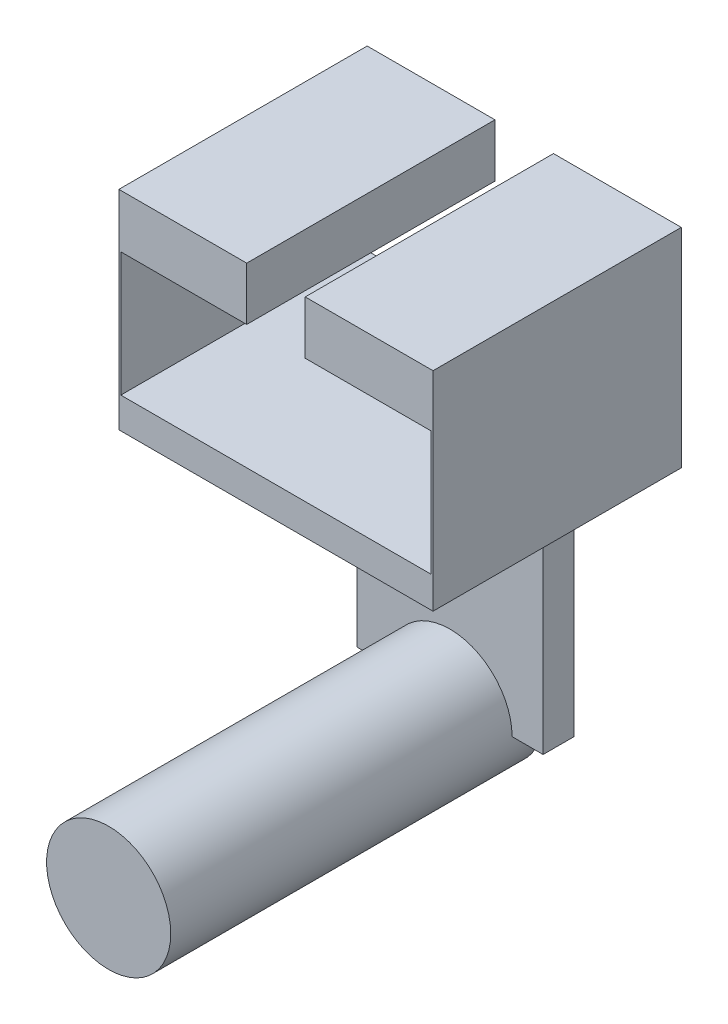
SolidWorks part; units mm, degrees
ref_plane "Front Plane" through (0, 0, 0) normal (0, 0, 1) x (1, 0, 0)
ref_plane "Top Plane" through (0, 0, 0) normal (0, 1, 0) x (1, 0, 0)
ref_plane "Right Plane" through (0, 0, 0) normal (1, 0, 0) x (0, 0, -1)
sketch "Sketch3" plane through (0, 0, 0) normal (0, 0, 1) x (1, 0, 0)
  circle A0 centre (0, 0) radius 12.7
  dimension "D1" = 25.4
extrude "Boss-Extrude1" add sketch "Sketch3" along normal blind 76.2
sketch "Sketch4" plane through (0, 0, 0) normal (0, 0, -1) x (-1, 0, 0)
  line L0 (0, 0) -> (19.05, 0)
  line L5 (19.05, 0) -> (19.05, 50.8)
  line L6 (19.05, 50.8) -> (-19.05, 50.8)
  line L7 (-19.05, 50.8) -> (-19.05, 0)
  line L8 (-19.05, 0) -> (0, 0)
  dimension "D1" = 50.8
  dimension "D2" = 38.1
extrude "Boss-Extrude2" add sketch "Sketch4" against normal blind 6.35 contours L7 L8 L0 L5 L6
sketch "Sketch6" plane through (0, 50.8, 0) normal (0, 1, 0) x (1, 0, 0)
  line L1 (-30.7019, 7.7865) -> (32.7981, 7.7865)
  line L2 (-30.7019, 7.7865) -> (-30.7019, -43.0135)
  line L3 (-30.7019, -43.0135) -> (32.7981, -43.0135)
  line L4 (32.7981, 7.7865) -> (32.7981, -43.0135)
  dimension "D1" = 63.5
  dimension "D2" = 50.8
extrude "Boss-Extrude3" add sketch "Sketch6" along normal blind 6.35
sketch "Sketch8" plane through (32.7981, 0, 0) normal (1, 0, 0) x (0, 0, -1)
  line L1 (-43.0135, 57.15) -> (7.7865, 57.15)
  line L2 (-43.0135, 57.15) -> (-43.0135, 50.8)
  line L3 (-43.0135, 50.8) -> (7.7865, 50.8)
  line L4 (7.7865, 57.15) -> (7.7865, 50.8)
sketch "Sketch9" plane through (32.7981, 0, 0) normal (1, 0, 0) x (0, 0, -1)
  line L1 (-43.0135, 57.15) -> (7.7865, 57.15)
  line L2 (-43.0135, 57.15) -> (-43.0135, 50.8)
  line L3 (-43.0135, 50.8) -> (7.7865, 50.8)
  line L4 (7.7865, 57.15) -> (7.7865, 50.8)
extrude "Boss-Extrude4" add sketch "Sketch9" along normal blind 0.3886
sketch "Sketch10" plane through (0, 57.15, 0) normal (0, 1, 0) x (1, 0, 0)
  line L0 (32.7981, -43.0135) -> (32.7981, 7.7865) construction
  line L1 (32.7981, 7.7865) -> (33.1867, 7.7865)
  line L2 (32.7981, 7.7865) -> (32.7981, -43.0135)
  line L3 (32.7981, -43.0135) -> (33.1867, -43.0135)
  line L4 (33.1867, 7.7865) -> (33.1867, -43.0135)
  line L5 (33.1867, 7.7865) -> (-30.7019, 7.7865) construction
extrude "Boss-Extrude5" add sketch "Sketch10" along normal blind 25.4
sketch "Sketch11" plane through (-30.7019, 0, 0) normal (-1, 0, 0) x (0, 0, 1)
  line L1 (-7.7865, 57.15) -> (43.0135, 57.15)
  line L2 (-7.7865, 57.15) -> (-7.7865, 50.8)
  line L3 (-7.7865, 50.8) -> (43.0135, 50.8)
  line L4 (43.0135, 57.15) -> (43.0135, 50.8)
extrude "Boss-Extrude6" add sketch "Sketch11" along normal blind 0.3886
sketch "Sketch13" plane through (0, 57.15, 0) normal (0, 1, 0) x (1, 0, 0)
  line L0 (-31.0906, -43.0135) -> (32.7981, -43.0135) construction
  line L1 (-31.0906, 7.7865) -> (-30.7019, 7.7865)
  line L2 (-31.0906, 7.7865) -> (-31.0906, -43.0135)
  line L3 (-31.0906, -43.0135) -> (-30.7019, -43.0135)
  line L4 (-30.7019, 7.7865) -> (-30.7019, -43.0135)
  dimension "D1" = 0.3886
extrude "Boss-Extrude7" add sketch "Sketch13" along normal blind 25.4
sketch "Sketch14" plane through (0, 82.55, 0) normal (0, 1, 0) x (1, 0, 0)
  line L1 (-31.0906, 7.7865) -> (-30.7019, 7.7865)
  line L2 (-31.0906, 7.7865) -> (-31.0906, -43.0135)
  line L3 (-31.0906, -43.0135) -> (-30.7019, -43.0135)
  line L4 (-30.7019, 7.7865) -> (-30.7019, -43.0135)
extrude "Boss-Extrude8" add sketch "Sketch14" along normal blind 10.8712
sketch "Sketch15" plane through (-30.7019, 0, 0) normal (1, 0, 0) x (0, 0, -1)
  line L0 (7.7865, 93.4212) -> (7.7865, 57.15) construction
  line L1 (-43.0135, 93.4212) -> (7.7865, 93.4212)
  line L2 (-43.0135, 93.4212) -> (-43.0135, 82.55)
  line L3 (-43.0135, 82.55) -> (7.7865, 82.55)
  line L4 (7.7865, 93.4212) -> (7.7865, 82.55)
  dimension "D1" = 10.8712
extrude "Boss-Extrude9" add sketch "Sketch15" along normal blind 25.7632
sketch "Sketch16" plane through (0, 82.55, 0) normal (0, 1, 0) x (1, 0, 0)
  line L1 (32.7981, 7.7865) -> (33.1867, 7.7865)
  line L2 (32.7981, 7.7865) -> (32.7981, -43.0135)
  line L3 (32.7981, -43.0135) -> (33.1867, -43.0135)
  line L4 (33.1867, 7.7865) -> (33.1867, -43.0135)
extrude "Boss-Extrude10" add sketch "Sketch16" along normal blind 10.8712
sketch "Sketch17" plane through (32.7981, 0, 0) normal (-1, 0, 0) x (0, 0, 1)
  line L0 (43.0135, 93.4212) -> (43.0135, 57.15) construction
  line L1 (-7.7865, 93.4212) -> (43.0135, 93.4212)
  line L2 (-7.7865, 93.4212) -> (-7.7865, 82.55)
  line L3 (-7.7865, 82.55) -> (43.0135, 82.55)
  line L4 (43.0135, 93.4212) -> (43.0135, 82.55)
  dimension "D1" = 10.8712
extrude "Boss-Extrude11" add sketch "Sketch17" along normal blind 25.7632
equation "\"Length_A\"= 3in"
equation "\"Diameter_A\"= 1in"
equation "\"Width_B\"= 1.5in"
equation "\"Length_B\"= 2in"
equation "\"Thickness_B\"= 0.25in"
equation "\"Length_C\"= 2.5in"
equation "\"Base_C\"= 2in"
equation "\"Height_C\"= 0.250in"
equation "\"Length_D\"= 2in"
equation "\"Base_D\"= 1.498in"
equation "\"Thickness_D\"=0.0153"
equation "\"Length_E\"= 2in"
equation "\"Base_E\"= 0.9990"
equation "\"Height_E\"= 0.428in"
equation "\"Sy\"= 36000"
equation "\"E\"= 29000000"
equation "\"deflection\"= 0.005in"
equation "\"D1@Sketch3\"=\"Diameter_A\""
equation "\"D1@Boss-Extrude1\"=\"Length_A\""
equation "\"D1@Sketch4\"=\"Length_B\""
equation "\"D1@Boss-Extrude2\"=\"Thickness_B\""
equation "\"D1@Sketch6\"=\"Length_C\""
equation "\"D2@Sketch6\"=\"Base_C\""
equation "\"D1@Boss-Extrude3\"=\"Height_C\""
equation "\"D1@Boss-Extrude4\"=\"Thickness_D\""
equation "\"D1@Boss-Extrude5\"=1in"
equation "\"D1@Boss-Extrude6\"=\"Thickness_D\""
equation "\"D1@Sketch13\"=\"Thickness_D\""
equation "\"D1@Boss-Extrude7\"=1in"
equation "\"D1@Boss-Extrude8\"=\"Height_E\""
equation "\"D1@Sketch15\"=\"Height_E\""
equation "\"D1@Boss-Extrude9\"=\"Base_E\"+\"Thickness_D\""
equation "\"D1@Boss-Extrude10\"=\"Height_E\""
equation "\"D1@Sketch17\"=\"Height_E\""
equation "\"D1@Boss-Extrude11\"=\"Thickness_D\"+\"Base_E\""
